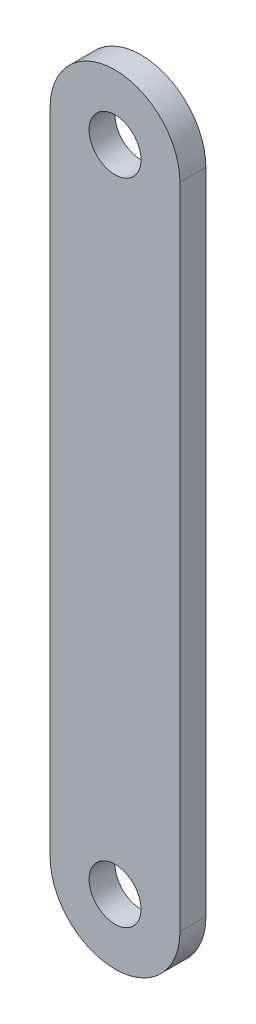
SolidWorks part; units mm, degrees
ref_plane "前视基准面" through (0, 0, 0) normal (0, 0, 1) x (1, 0, 0)
ref_plane "上视基准面" through (0, 0, 0) normal (0, 1, 0) x (1, 0, 0)
ref_plane "右视基准面" through (0, 0, 0) normal (1, 0, 0) x (0, 0, -1)
sketch "草图1" plane through (0, 0, 0) normal (0, 0, 1) x (1, 0, 0)
  line L2 (-5, 25) -> (-5, -25)
  line L4 (5, 25) -> (5, -25)
  line L5 (0, -30) -> (0, 49.1891) construction
  line L6 (-5, 0) -> (5, 0) construction
  arc A0 (-5, -25) -> (5, -25) centre (0, -25) ccw
  arc A1 (-5, 25) -> (5, 25) centre (0, 25) cw
  circle A2 centre (0, -25) radius 2
  circle A3 centre (0, 25) radius 2
  point P0 (0, 0)
  dimension "D2" = 10
  dimension "D1" = 4
  dimension "D3" = 4
  dimension "D4" = 50
extrude "凸台-拉伸1" add sketch "草图1" along normal blind 2
